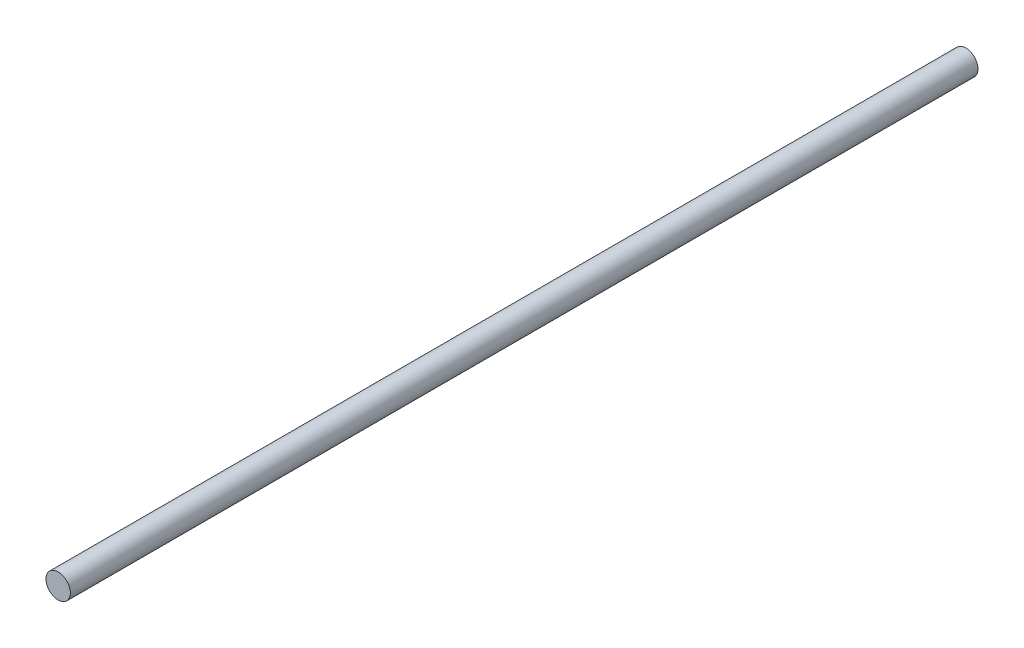
SolidWorks part; units mm, degrees
ref_plane "Front Plane" through (0, 0, 0) normal (0, 0, 1) x (1, 0, 0)
ref_plane "Top Plane" through (0, 0, 0) normal (0, 1, 0) x (1, 0, 0)
ref_plane "Right Plane" through (0, 0, 0) normal (1, 0, 0) x (0, 0, -1)
sketch "Sketch1" plane through (0, 0, 0) normal (0, 0, 1) x (1, 0, 0)
  circle A0 centre (0, 0) radius 12.7
  dimension "D1" = 25.4
extrude "Boss-Extrude1" add sketch "Sketch1" along normal blind 944.88
